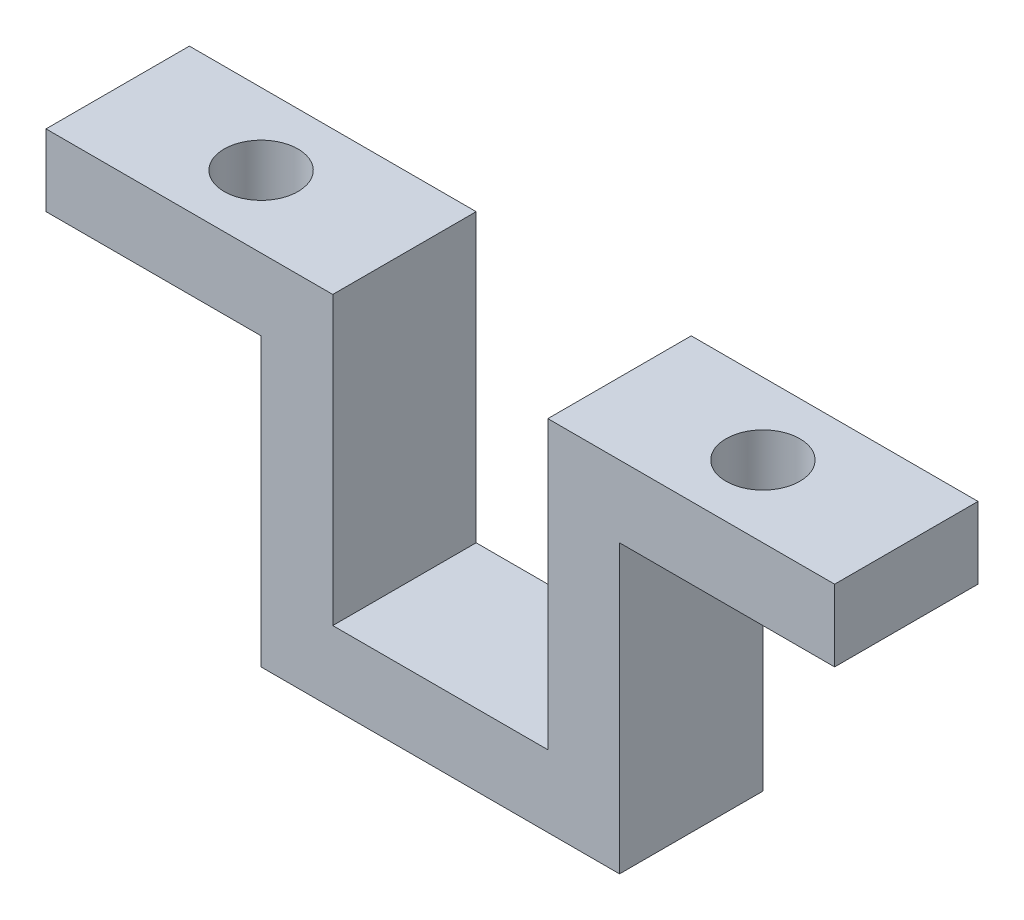
SolidWorks part; units mm, degrees
ref_plane "Front Plane" through (0, 0, 0) normal (0, 0, 1) x (1, 0, 0)
ref_plane "Top Plane" through (0, 0, 0) normal (0, 1, 0) x (1, 0, 0)
ref_plane "Right Plane" through (0, 0, 0) normal (1, 0, 0) x (0, 0, -1)
sketch "Sketch1" plane through (0, 0, 0) normal (0, 0, 1) x (1, 0, 0)
  line L0 (0, 0) -> (20, 0)
  line L1 (20, 0) -> (20, -20)
  line L2 (20, -20) -> (35, -20)
  line L3 (35, -20) -> (35, 0)
  line L4 (35, 0) -> (55, 0)
  line L5 (40, -5) -> (40, -25)
  line L6 (40, -25) -> (15, -25)
  line L7 (15, -25) -> (15, -5)
  line L11 (15, -5) -> (0, -5)
  line L12 (0, 0) -> (0, -5)
  line L15 (40, -5) -> (55, -5)
  line L16 (55, 0) -> (55, -5)
  point P0 (25, -25.8135)
  point P7 (10, 0)
  point P15 (0, 0)
  point P17 (45, 0)
  dimension "D1" = 35
  dimension "D2" = 20
  dimension "D3" = 5
  dimension "D4" = 5
  dimension "D5" = 5
  dimension "D6" = 25
extrude "Boss-Extrude1" add sketch "Sketch1" along normal blind 10
sketch "Sketch2" plane through (0, 0, 0) normal (0, 1, 0) x (1, 0, 0)
  line L0 (0, 0) -> (20, -10) construction
  line L1 (20, 0) -> (0, -10) construction
  line L2 (27.5, 0) -> (27.5, 50000) construction
  line L3 (35, 0) -> (20, 0) construction
  circle A0 centre (10, -5) radius 2.575
  circle A2 centre (45, -5) radius 2.575
  point P4 (10, -5)
  point P5 (0, 0)
  point P6 (0, 0)
  point P7 (43.5, -5)
  point P14 (27.5, 0)
  point P17 (43.5, -5)
  point P18 (43.5, -5)
  point P25 (0, 0)
  dimension "D1" = 5.15
  dimension "D2" = 0
extrude "Cut-Extrude1" cut sketch "Sketch2" against normal through all
